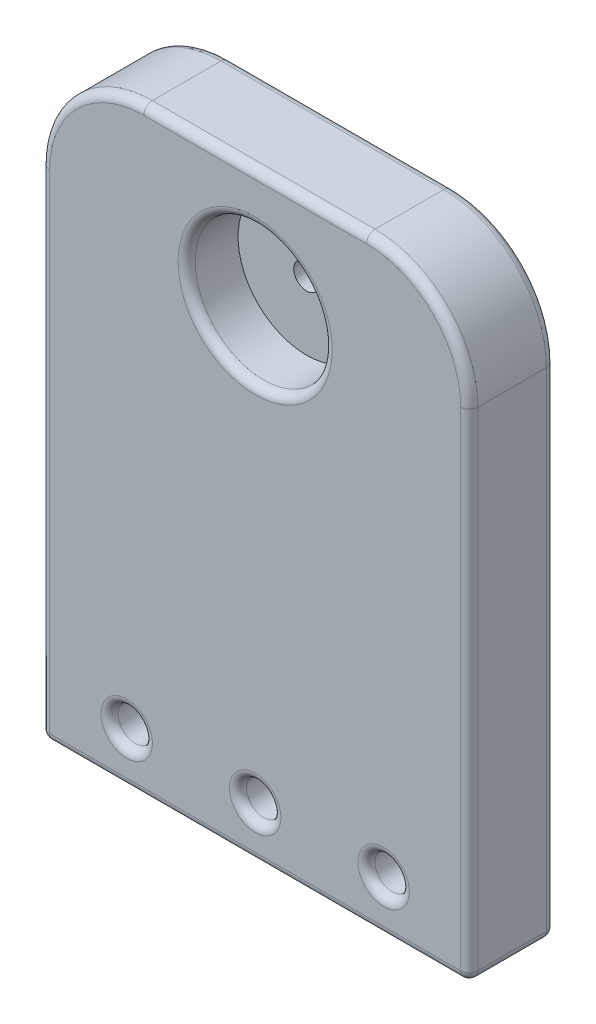
SolidWorks part; units mm, degrees
material "PLA"
ref_plane "Alzado" through (0, 0, 0) normal (0, 0, 1) x (1, 0, 0)
ref_plane "Planta" through (0, 0, 0) normal (0, 1, 0) x (1, 0, 0)
ref_plane "Vista lateral" through (0, 0, 0) normal (1, 0, 0) x (0, 0, -1)
sketch "Sketch1" plane through (0, 0, 0) normal (0, 0, 1) x (1, 0, 0)
  line L1 (25, 35) -> (-25, 35)
  line L2 (25, 35) -> (25, -35)
  line L3 (25, -35) -> (-25, -35)
  line L4 (-25, 35) -> (-25, -35)
  line L5 (25, 35) -> (-25, -35) construction
  line L6 (25, -35) -> (-25, 35) construction
  point P0 (0, 0)
  dimension "D1" = 50
  dimension "D2" = 70
extrude "Boss-Extrude1" add sketch "Sketch1" along normal blind 10
sketch "Sketch6" plane through (0, 0, 0) normal (0, 0, -1) x (-1, 0, 0)
  line L0 (-25, 35) -> (25, 35) construction
  line L1 (-25, -35) -> (-25, 35) construction
  circle A0 centre (0, 21.25) radius 1.5
  dimension "D1" = 3
  dimension "D2" = 13.75
  dimension "D3" = 25
extrude "Cut-Extrude1" cut sketch "Sketch6" against normal through all
sketch "Sketch8" plane through (0, 0, 10) normal (0, 0, 1) x (1, 0, 0)
  circle A0 centre (0, 21.25) radius 8
  dimension "D1" = 16
extrude "Cut-Extrude3" cut sketch "Sketch8" against normal blind 6
fillet "Fillet1" radius 12 2 edges at (25, 35, 5) (-25, 35, 5)
sketch "Sketch9" plane through (0, 0, 0) normal (0, 0, -1) x (-1, 0, 0)
  line L0 (-25, -29) -> (25, -29) construction
  line L1 (-25, -35) -> (-25, 23) construction
  line L2 (25, 23) -> (25, -35) construction
  line L3 (25, -35) -> (-25, -35) construction
  circle A0 centre (-15, -29) radius 2
  circle A1 centre (0, -29) radius 2
  circle A2 centre (15, -29) radius 2
  dimension "D2" = 4
  dimension "D3" = 4
  dimension "D4" = 4
  dimension "D1" = 6
  dimension "D5" = 10
  dimension "D6" = 10
extrude "Cut-Extrude4" cut sketch "Sketch9" against normal blind 14
sketch "Sketch10" plane through (0, 0, 0) normal (0, 0, -1) x (-1, 0, 0)
  circle A0 centre (-15, -29) radius 3.875
  circle A1 centre (0, -29) radius 3.875
  circle A2 centre (15, -29) radius 3.875
  dimension "D1" = 7.75
  dimension "D2" = 7.75
  dimension "D3" = 7.75
extrude "Cut-Extrude5" cut sketch "Sketch10" against normal blind 4
fillet "Fillet2" radius 1 22 edges at (25, -35, 5) (-25, -35, 5) (0, -35, 10) (-25, -6, 10) (-21.4853, 31.4853, 10) (0, 35, 10) (21.4853, 31.4853, 10) (25, -6, 10) (8, 21.25, 10) (-17, -29, 10) (-2, -29, 10) (13, -29, 10) (-21.4853, 31.4853, 0) (-25, -6, 0) (0, -35, 0) (25, -6, 0) (21.4853, 31.4853, 0) (0, 35, 0) (-1.5, 21.25, 0) (-18.875, -29, 0) (-3.875, -29, 0) (11.125, -29, 0)
